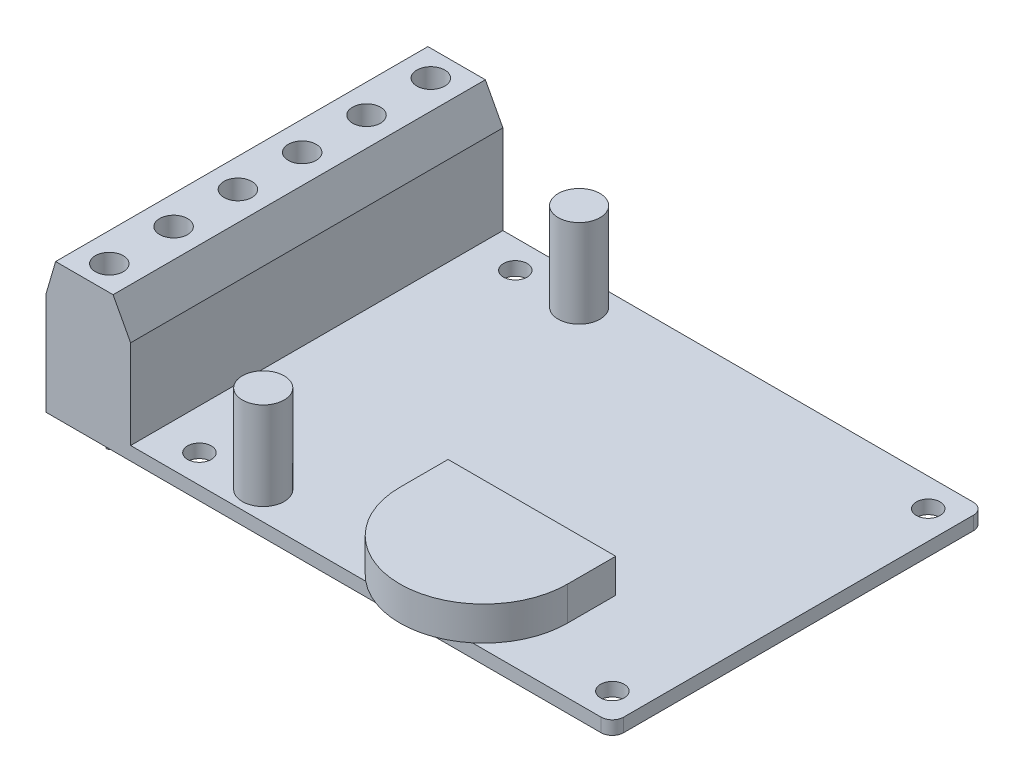
SolidWorks part; units mm, degrees
ref_plane "前视基准面" through (0, 0, 0) normal (0, 0, 1) x (1, 0, 0)
ref_plane "上视基准面" through (0, 0, 0) normal (0, 1, 0) x (1, 0, 0)
ref_plane "右视基准面" through (0, 0, 0) normal (1, 0, 0) x (0, 0, -1)
sketch "草图2" plane through (0, 0, 0) normal (0, 1, 0) x (1, 0, 0)
  line L0 (0, 0) -> (37.347, 0) construction
  line L1 (0, 0) -> (0, -35.97) construction
  line L3 (1, 0) -> (49.2, 0)
  line L4 (0, -1) -> (0, -32)
  line L5 (1, -33) -> (49.2, -33)
  line L6 (50.2, -1) -> (50.2, -32)
  arc A0 (1, 0) -> (0, -1) centre (1, -1) ccw
  arc A1 (0, -32) -> (1, -33) centre (1, -32) ccw
  arc A2 (49.2, -33) -> (50.2, -32) centre (49.2, -32) ccw
  arc A3 (49.2, 0) -> (50.2, -1) centre (49.2, -1) cw
  point P12 (0, -33)
  point P15 (50.2, -33)
  point P18 (50.2, 0)
  dimension "D3" = 1
  dimension "D1" = 50.2
  dimension "D2" = 33
extrude "凸台-拉伸1" add sketch "草图2" along normal blind 1.2
sketch "草图3" plane through (0, 0, 0) normal (0, 0, 1) x (1, 0, 0)
  line L0 (0, 0) -> (0, 9.0843)
  line L1 (0.8517, 12) -> (5.9459, 12)
  line L2 (7.5, 9.0843) -> (7.5, 0)
  line L3 (1, 0) -> (49.2, 0) construction
  line L4 (0.8517, 12) -> (0, 9.0843)
  line L5 (3.75, 12) -> (3.75, -2.4652) construction
  line L6 (5.9459, 12) -> (7.5, 9.0843)
  line L7 (7.5, 0) -> (0, 0)
  dimension "D1" = 12
  dimension "D2" = 7.5
extrude "凸台-拉伸3" add sketch "草图3" along normal blind 33 separate body
sketch "草图4" plane through (0, 12, 0) normal (0, 1, 0) x (1, 0, 0)
  line L0 (0.8517, -16.5) -> (38.1743, -16.5) construction
  line L1 (0.8517, -33) -> (0.8517, 0) construction
  line L2 (3.3988, 0) -> (3.3988, -35.8947) construction
  line L3 (5.9459, 0) -> (0.8517, 0) construction
  circle A0 centre (3.3988, -2.2884) radius 1.238
  circle A1 centre (3.3988, -7.9884) radius 1.238
  circle A2 centre (3.3988, -13.6884) radius 1.238
  circle A3 centre (3.3988, -19.3884) radius 1.238
  circle A4 centre (3.3988, -25.0884) radius 1.238
  circle A5 centre (3.3988, -30.7884) radius 1.238
  dimension "D1" = 6
extrude "切除-拉伸1" cut sketch "草图4" against normal blind 2
sketch "草图5" plane through (0, 1.2, 0) normal (0, 1, 0) x (1, 0, 0)
  line L0 (50.2, -32) -> (50.2, -1) construction
  line L1 (49.2, 0) -> (1, 0) construction
  line L2 (50.2, -16.5) -> (22.4036, -16.5) construction
  circle A0 centre (47.7, -2.5) radius 1.05
  circle A1 centre (47.7, -30.5) radius 1.05
  circle A2 centre (11.1, -2.5) radius 1.05
  circle A3 centre (11.1, -30.5) radius 1.05
  dimension "D1" = 2.1
  dimension "D2" = 2.5
  dimension "D3" = 2.5
  dimension "D5" = 36.6
  dimension "D4" = 2
extrude "切除-拉伸2" cut sketch "草图5" against normal blind 2
sketch "草图6" plane through (0, 0, 0) normal (0, -1, 0) x (1, 0, 0)
  circle A12 centre (3.3988, 25.0884) radius 0.4351
  circle A13 centre (3.3988, 19.3884) radius 0.4351
  circle A14 centre (3.3988, 13.6884) radius 0.4351
  circle A15 centre (3.3988, 7.9884) radius 0.4351
  circle A16 centre (3.3988, 2.2884) radius 0.4351
  circle A17 centre (3.3988, 30.7884) radius 0.4351
extrude "凸台-拉伸4" add sketch "草图6" along normal blind 0.1
sketch "草图7" plane through (0, -0.1, 0) normal (0, -1, 0) x (1, 0, 0)
  circle A0 centre (3.3988, 30.7884) radius 0.2215
  circle A1 centre (3.3988, 25.0884) radius 0.2215
  circle A2 centre (3.3988, 19.3884) radius 0.2215
  circle A3 centre (3.3988, 13.6884) radius 0.2215
  circle A4 centre (3.3988, 7.9884) radius 0.2215
  circle A5 centre (3.3988, 2.2884) radius 0.2215
extrude "凸台-拉伸5" add sketch "草图7" along normal blind 2
sketch "草图8" plane through (0, 0, 0) normal (0, -1, 0) x (1, 0, 0)
  line L0 (18.0643, 16.5) -> (35.5172, 16.5) construction
  text T0 "Ruige"
extrude "凸台-拉伸6" add sketch "草图8" along normal blind 0.01
sketch "草图11" plane through (0, 1.2, 0) normal (0, 1, 0) x (1, 0, 0)
  line L0 (25.64, -23) -> (40.5, -23)
  line L1 (40.5, -23) -> (40.5, -27.27)
  line L2 (25.64, -23) -> (25.64, -27.27)
  line L3 (25.64, -27.27) -> (33.07, -27.27) construction
  line L4 (7.5, -33) -> (49.2, -33) construction
  line L5 (50.2, -32) -> (50.2, -1) construction
  arc A0 (25.64, -27.27) -> (40.5, -27.27) centre (33.07, -27.27) ccw
  dimension "D1" = 10
  dimension "D2" = 7.43
  dimension "D3" = 4.27
  dimension "D4" = 9.7
extrude "凸台-拉伸8" add sketch "草图11" along normal blind 3
sketch "草图10" plane through (0, 1.2, 0) normal (0, 1, 0) x (1, 0, 0)
  line L0 (16.7553, -16.5) -> (16.7553, -1.0833) construction
  line L3 (16.7553, -16.5) -> (34.7254, -16.5) construction
  circle A0 centre (16.7553, -2.5) radius 1.8546
  circle A1 centre (16.7553, -30.5) radius 1.8546
extrude "凸台-拉伸7" add sketch "草图10" along normal blind 7.8
